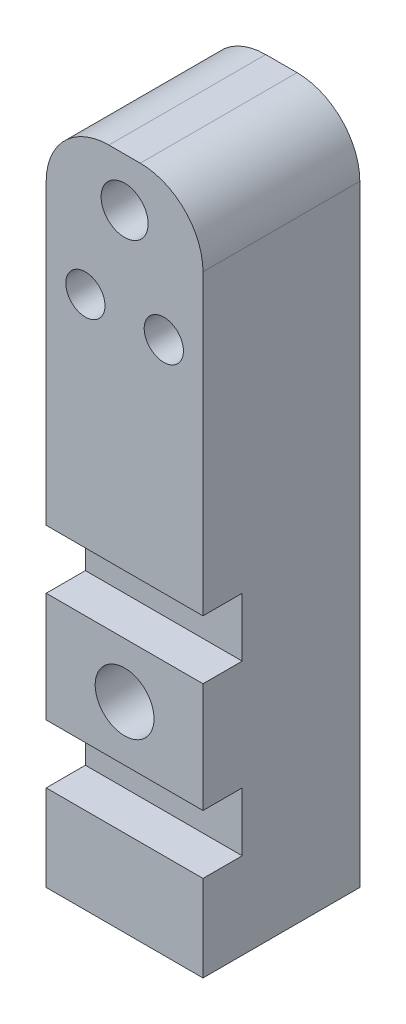
SolidWorks part; units mm, degrees
ref_plane "Front Plane" through (0, 0, 0) normal (0, 0, 1) x (1, 0, 0)
ref_plane "Top Plane" through (0, 0, 0) normal (0, 1, 0) x (1, 0, 0)
ref_plane "Right Plane" through (0, 0, 0) normal (1, 0, 0) x (0, 0, -1)
sketch "Sketch1" plane through (0, 0, 0) normal (0, 1, 0) x (1, 0, 0)
  point P0 (-7.1017, 0)
sketch "Sketch2" plane through (0, 0, 0) normal (0, 1, 0) x (1, 0, 0)
  line L1 (-0.5, 0.5) -> (0.5, 0.5)
  line L2 (-0.5, 0.5) -> (-0.5, -0.5)
  line L3 (-0.5, -0.5) -> (0.5, -0.5)
  line L4 (0.5, 0.5) -> (0.5, -0.5)
  line L5 (-0.5, 0.5) -> (0.5, -0.5) construction
  line L6 (-0.5, -0.5) -> (0.5, 0.5) construction
  point P0 (0, 0)
  dimension "D1" = 1
extrude "Boss-Extrude1" add sketch "Sketch2" along normal blind 4.3
sketch "Sketch3" plane through (0, 0, 0) normal (0, -1, 0) x (1, 0, 0)
  circle A0 centre (0, 0) radius 0.1
  dimension "D1" = 0.2
extrude "Cut-Extrude1" cut sketch "Sketch3" against normal blind 0.7
sketch "Sketch4" plane through (0, 0, 0.5) normal (0, 0, 1) x (1, 0, 0)
  line L0 (0.5, 4.3) -> (0.5, 0) construction
  line L1 (-0.5, 1.625) -> (0.5, 1.625)
  line L2 (-0.5, 1.625) -> (-0.5, 2)
  line L3 (-0.5, 2) -> (0.5, 2)
  line L4 (0.5, 1.625) -> (0.5, 2)
  line L5 (-0.5, 1.625) -> (0.5, 2) construction
  line L6 (-0.5, 2) -> (0.5, 1.625) construction
  line L8 (-0.5, 0) -> (0.5, 0) construction
  point P0 (0, 1.8125)
  dimension "D1" = 1.625
  dimension "D2" = 0.375
extrude "Cut-Extrude2" cut sketch "Sketch4" against normal blind 0.25
sketch "Sketch5" plane through (0, 0, 0.5) normal (0, 0, 1) x (1, 0, 0)
  line L0 (-0.5, 1.625) -> (0.5, 1.625) construction
  line L1 (-0.5, 0) -> (0.5, 0) construction
  line L2 (-0.5, 1.625) -> (-0.5, 0) construction
  circle A0 centre (0, 1.275) radius 0.1875
  dimension "D2" = 0.375
  dimension "D4" = 0.5
  dimension "D1" = 0.35
  dimension "D3" = 1.275
extrude "Cut-Extrude3" cut sketch "Sketch5" against normal blind 1
sketch "Sketch6" plane through (0, 0, 0.5) normal (0, 0, 1) x (1, 0, 0)
  line L0 (0.5, 1.625) -> (0.5, 0) construction
  line L1 (-0.5, 0.925) -> (0.5, 0.925)
  line L2 (-0.5, 0.925) -> (-0.5, 0.55)
  line L3 (-0.5, 0.55) -> (0.5, 0.55)
  line L4 (0.5, 0.925) -> (0.5, 0.55)
  line L5 (-0.5, 0.925) -> (0.5, 0.55) construction
  line L6 (-0.5, 0.55) -> (0.5, 0.925) construction
  line L7 (-0.5, 0) -> (0.5, 0) construction
  point P0 (0, 0.7375)
  dimension "D1" = 0.375
  dimension "D2" = 0.925
sketch "Sketch7" plane through (0, 0, 0.5) normal (0, 0, 1) x (1, 0, 0)
  line L0 (-0.5, 4.3) -> (0.5, 4.3) construction
  line L1 (-0.5, 4.3) -> (-0.5, 2) construction
  circle A0 centre (0, 3.99) radius 0.15
  dimension "D2" = 0.3
  dimension "D1" = 0.31
  dimension "D3" = 0.5
extrude "Cut-Extrude6" cut sketch "Sketch7" against normal blind 0.65
sketch "Sketch8" plane through (0, 0, 0.5) normal (0, 0, 1) x (1, 0, 0)
  line L0 (-0.5, 4.3) -> (0.5, 4.3) construction
  line L1 (0.5, 4.3) -> (0.5, 2) construction
  line L2 (-0.5, 4.3) -> (-0.5, 2) construction
  circle A1 centre (-0.25, 3.4) radius 0.125
  circle A2 centre (0.25, 3.4) radius 0.125
  point P4 (0, 0)
  dimension "D1" = 0.9
  dimension "D4" = 0.25
  dimension "D2" = 0.25
  dimension "D3" = 0.25
extrude "Cut-Extrude7" cut sketch "Sketch8" against normal blind 1
fillet "Fillet1" radius 0.4 2 edges at (0.5, 4.3, 0) (-0.5, 4.3, 0)
sketch "Sketch10" plane through (0, 0, 0.5) normal (0, 0, 1) x (1, 0, 0)
  point P0 (0, 0.7375)
extrude "Cut-Extrude8" cut sketch "Sketch6" against normal blind 0.25
